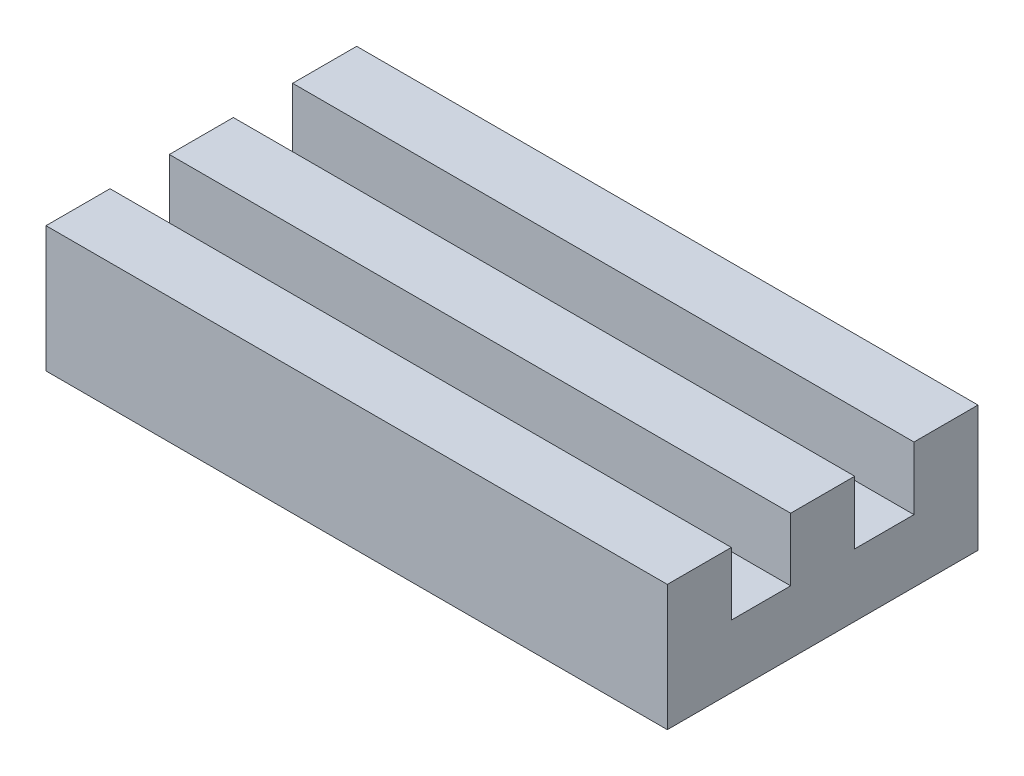
SolidWorks part; units mm, degrees
ref_plane "Front Plane" through (0, 0, 0) normal (0, 0, 1) x (1, 0, 0)
ref_plane "Top Plane" through (0, 0, 0) normal (0, 1, 0) x (1, 0, 0)
ref_plane "Right Plane" through (0, 0, 0) normal (1, 0, 0) x (0, 0, -1)
sketch "Sketch1" plane through (0, 0, 0) normal (0, 1, 0) x (1, 0, 0)
  line L0 (0, 0) -> (0, 7.9)
  line L1 (0, 0) -> (15.8, 0)
  line L2 (0, 7.9) -> (15.8, 7.9)
  line L3 (15.8, 7.9) -> (15.8, 0)
  dimension "D1" = 7.9
  dimension "D2" = 15.8
extrude "Boss-Extrude1" add sketch "Sketch1" along normal blind 3.2
sketch "Sketch2" plane through (0, 0, 0) normal (-1, 0, 0) x (0, 0, 1)
  line L0 (-4.7641, 3.2) -> (-3.1359, 3.2)
  line L1 (-7.9, 3.2) -> (0, 3.2) construction
  line L2 (0, 1.6) -> (-7.9, 1.6) construction
  line L3 (0, 3.2) -> (0, 0) construction
  line L4 (-7.9, 3.2) -> (-7.9, 0) construction
  line L5 (-3.1359, 3.2) -> (-3.1359, 1.6)
  line L6 (-3.1359, 1.6) -> (-1.6282, 1.6)
  line L7 (-1.6282, 1.6) -> (-1.6282, 3.2)
  line L8 (-1.6282, 3.2) -> (0, 3.2)
  line L9 (0, 3.2) -> (0, 1.6)
  line L10 (-4.7641, 3.2) -> (-4.7641, 1.6)
  line L11 (-4.7641, 1.6) -> (-6.2718, 1.6)
  line L12 (-6.2718, 1.6) -> (-6.2718, 3.2)
  line L13 (-6.2718, 3.2) -> (-7.9, 3.2)
  line L14 (-7.9, 3.2) -> (-7.9, 1.6363)
  line L15 (-7.9, 1.6363) -> (-7.9, 1.6)
  line L16 (-7.9, 1.6) -> (-6.2718, 1.6)
  line L17 (-4.7641, 1.6) -> (-3.1359, 1.6)
  line L18 (-1.6282, 1.6) -> (0, 1.6)
  line L19 (-6.2718, 3.2) -> (-4.7641, 3.2)
  line L20 (-3.1359, 3.2) -> (-1.6282, 3.2)
  point P5 (-3.95, 2.983)
  line M19 (0, 3.2) -> (-7.9, 3.2)
extrude "Cut-Extrude1" cut sketch "Sketch2" against normal up to surface (15.8 mm away) contours L6 L7 L5 M19 | L12 L11 L10 M19 up to face at (15.8, 1.6, -3.95)
